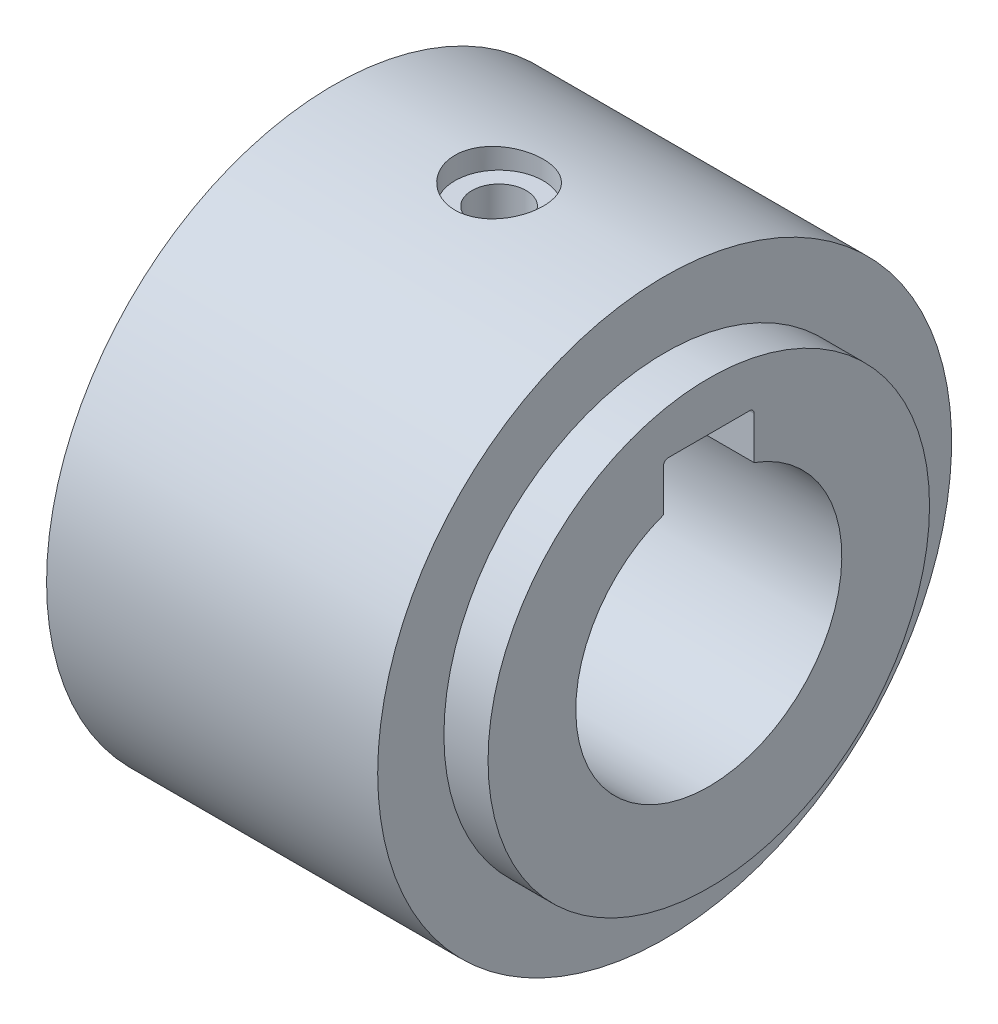
SolidWorks part; units mm, degrees
ref_plane "Front Plane" through (0, 0, 0) normal (0, 0, 1) x (1, 0, 0)
ref_plane "Top Plane" through (0, 0, 0) normal (0, 1, 0) x (1, 0, 0)
ref_plane "Right Plane" through (0, 0, 0) normal (1, 0, 0) x (0, 0, -1)
ref_plane "Plane1" through (0, 0, 0) normal (0, 0, -1) x (-1, 0, 0)
sketch "Sketch1" plane through (0, 0, 0) normal (0, 0, -1) x (-1, 0, 0)
  line L0 (-9.5, 10) -> (-9.5, 0)
  line L1 (-9.5, 0) -> (9.5, 0)
  line L2 (9.5, 0) -> (9.5, 10)
  line L3 (9.5, 10) -> (7.5, 10)
  line L4 (7.5, 10) -> (7.5, 13)
  line L5 (-7.5, 13) -> (-7.5, 10)
  line L6 (-7.5, 10) -> (-9.5, 10)
  line L7 (-9.5, 0) -> (9.5, 0) construction
  line L8 (0, 0) -> (0, 7.3725) construction
  line L9 (-7.5, 13) -> (7.5, 13)
  dimension "D1" = 10
  dimension "D2" = 19
  dimension "D3" = 2
  dimension "D4" = 2
  dimension "D5" = 13
revolve "Revolve1" add sketch "Sketch1" angle 360 about L7
sketch "Sketch2" plane through (-9.5, 0, 0) normal (-1, 0, 0) x (0, 0, 1)
  line L0 (2.05, 5.6389) -> (2.05, 7.8)
  line L1 (2.05, 7.8) -> (-2.05, 7.8)
  line L2 (-2.05, 7.8) -> (-2.05, 5.6389)
  line L3 (0, 0) -> (0, 14.2606) construction
  arc A0 (2.05, 5.6389) -> (-2.05, 5.6389) centre (0, 0) ccw
  circle A1 centre (0, 0) radius 6 construction
  point P7 (0, 7.8)
  dimension "D1" = 4.1
extrude "Cut-Extrude1" cut sketch "Sketch2" against normal through all
sketch "Sketch3" plane through (0, 0, 0) normal (0, 0, -1) x (-1, 0, 0)
  line L0 (-9.5, 6.025) -> (-9.5, 0)
  line L1 (-9.5, 0) -> (9.5, 0)
  line L2 (9.5, 0) -> (9.5, 6.025)
  line L3 (9.5, 6.025) -> (-9.5, 6.025)
  line L4 (-9.5, 0) -> (9.5, 0) construction
  line L5 (9.5, -10) -> (9.5, 10) construction
  line L6 (-9.5, 10) -> (-9.5, -10) construction
  dimension "D1" = 6.025
revolve "0.5mm clearance" cut sketch "Sketch3" angle 360 about L4
ref_plane "Plane2" through (0, 0, -35.2639) normal (0, 0, -1) x (-1, 0, 0)
ref_plane "Plane3" through (0, 35.2639, 0) normal (0, 1, 0) x (1, 0, 0)
hole_wizard "CBORE for M2 Hex Head Machine Screw2" positions "Sketch7" profile "Sketch6" counterbore size "M2" standard "ANSI Metric"
sketch "Sketch7" plane through (0, 35.2639, 0) normal (0, 1, 0) x (1, 0, 0)
  point P0 (0, 0)
sketch "Sketch6" plane through (0, 35.2639, 0) normal (1, 0, 0) x (0, 0, 1)
  line L0 (0, 0) -> (0, 27.4639)
  line L1 (0, 27.4639) -> (1.2295, 27.4639)
  line L3 (1.2295, 27.4639) -> (1.2295, 23.2639)
  line L4 (1.2295, 23.2639) -> (2, 23.2639)
  line L5 (2, 23.2639) -> (2, 0)
  line L7 (2, 0) -> (0, 0)
  line L11 (0, -6.35) -> (0, 107.95) construction
  dimension "Thru Hole Dia." = 2.459
  dimension "Thru Hole Depth" = 27.4639
  dimension "C'Bore Dia." = 4
  dimension "C'Bore Depth" = 23.2639
fillet "Fillet1" radius 0.2 2 edges at (0, 7.8, -2.05) (0, 7.8, 2.05)
